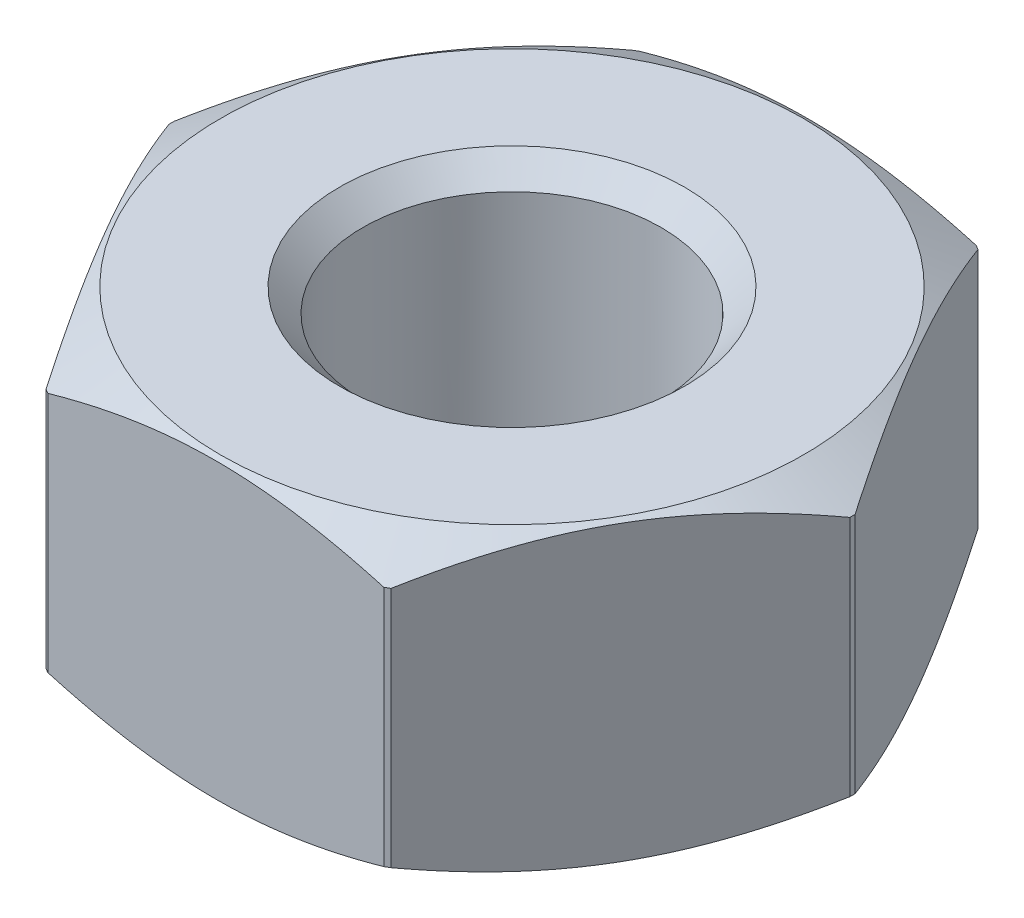
SolidWorks part; units mm, degrees
ref_plane "Front" through (0, 0, 0) normal (0, 0, 1) x (1, 0, 0)
ref_plane "Top" through (0, 0, 0) normal (0, 1, 0) x (1, 0, 0)
ref_plane "Right" through (0, 0, 0) normal (1, 0, 0) x (0, 0, -1)
sketch "Sketch1" plane through (0, 0, 0) normal (1, 0, 0) x (0, 0, -1)
  line L0 (0, 12.0296) -> (0, 0) construction
  line L1 (0, 0) -> (13.1556, 0) construction
  line L2 (3.2, 3.2) -> (3.2, -3.2)
  line L3 (3.2, -3.2) -> (6.25, -3.2)
  line L4 (6.25, -3.2) -> (7.3, -2.5938)
  line L5 (7.3, -2.5938) -> (7.3, 2.5938)
  line L6 (7.3, 2.5938) -> (6.25, 3.2)
  line L7 (6.25, 3.2) -> (3.2, 3.2)
  dimension "D1" = 6.4
  dimension "D2" = 6.4
  dimension "D3" = 30
  dimension "D4" = 14.6
  dimension "D5" = 12.5
revolve "Revolve1" add sketch "Sketch1" angle 360 about L0
cosmetic thread "Cosmetic Thread1" parameters "D2"=8
sketch "Sketch2" plane through (0, 3.2, 0) normal (0, 1, 0) x (1, 0, 0)
  line L1 (7.3323, 0) -> (3.6662, 6.35)
  line L2 (3.6662, 6.35) -> (-3.6662, 6.35)
  line L3 (-3.6662, 6.35) -> (-7.3323, 0)
  line L4 (-7.3323, 0) -> (-3.6662, -6.35)
  line L5 (-3.6662, -6.35) -> (3.6662, -6.35)
  line L6 (3.6662, -6.35) -> (7.3323, 0)
  circle A0 centre (0, 0) radius 6.35 construction
  dimension "D1" = 12.7
extrude "Cut-Extrude1" cut sketch "Sketch2" against normal up to next (6.4 mm away) flip side to cut
chamfer "Chamfer1" distance 0.5 angle 45 2 edges at (0, -3.2, 3.2) (0, 3.2, 3.2)
